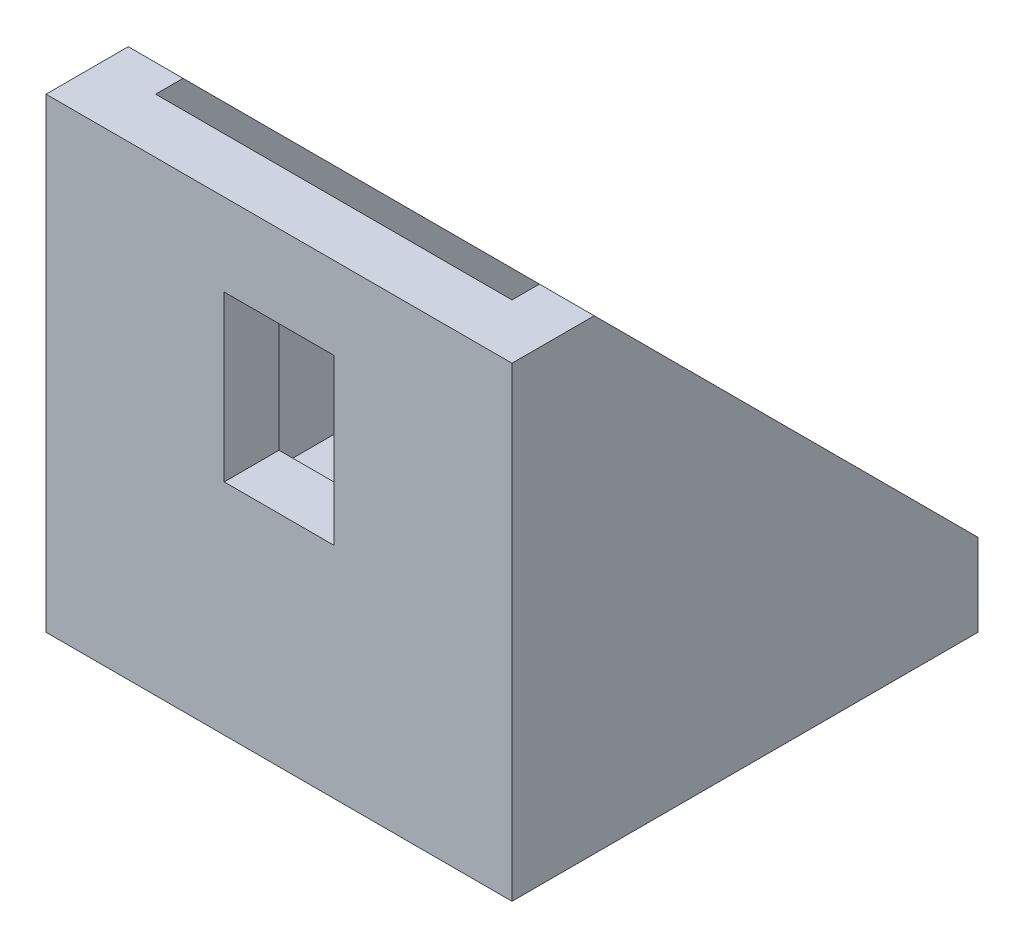
SolidWorks part; units mm, degrees
ref_plane "Front Plane" through (0, 0, 0) normal (0, 0, 1) x (1, 0, 0)
ref_plane "Top Plane" through (0, 0, 0) normal (0, 1, 0) x (1, 0, 0)
ref_plane "Right Plane" through (0, 0, 0) normal (1, 0, 0) x (0, 0, -1)
sketch "Sketch1" plane through (0, 0, 0) normal (1, 0, 0) x (0, 0, -1)
  line L0 (3, 17) -> (0, 17)
  line L1 (0, 17) -> (0, 0)
  line L2 (0, 0) -> (17, 0)
  line L3 (17, 0) -> (17, 3)
  line L4 (17, 3) -> (3, 17)
  dimension "D1" = 3
  dimension "D2" = 17
extrude "Body" add sketch "Sketch1" along normal mid plane 17
sketch "Sketch2" plane through (0, 0, -17) normal (0, 0, -1) x (-1, 0, 0)
  line L0 (-8.5, 3) -> (8.5, 3) construction
  line L1 (-6.5, 3) -> (6.5, 3)
  line L2 (-6.5, 3) -> (-6.5, 17)
  line L3 (-6.5, 17) -> (6.5, 17)
  line L4 (6.5, 3) -> (6.5, 17)
  line L5 (-8.5, 17) -> (8.5, 17) construction
  line L6 (8.5, 3) -> (8.5, 17) construction
  dimension "D1" = 2
  dimension "D2" = 2
extrude "Extusion" cut sketch "Sketch2" against normal offset from surface (15 mm away) 2 up to face at (0, 8.5, 0)
sketch "Sketch3" plane through (0, 0, -2) normal (0, 0, -1) x (-1, 0, 0)
  line L0 (-6.5, 17) -> (6.5, 17) construction
  line L7 (2, 8) -> (-2, 8)
  line L8 (2, 8) -> (2, 14)
  line L9 (2, 14) -> (-2, 14)
  line L10 (-2, 8) -> (-2, 14)
  line L11 (-6.5, 3) -> (-6.5, 17) construction
  line L13 (6.5, 17) -> (6.5, 3) construction
  point P6 (-2, 11)
  dimension "D1" = 3
  dimension "D2" = 4
  dimension "D3" = 6
  dimension "D4" = 4.5
extrude "Hole_A" cut sketch "Sketch3" against normal through all
sketch "Sketch4" plane through (0, 3, 0) normal (0, 1, 0) x (1, 0, 0)
  line L0 (6.5, 17) -> (-6.5, 17) construction
  line L3 (-2, 8) -> (2, 8)
  line L5 (-2, 8) -> (-2, 14)
  line L6 (-2, 14) -> (2, 14)
  line L7 (2, 8) -> (2, 14)
  line L8 (-6.5, 2) -> (-6.5, 17) construction
  dimension "D1" = 3
  dimension "D2" = 4
  dimension "D3" = 6
  dimension "D4" = 4.5
extrude "Hole_B" cut sketch "Sketch4" against normal blind 17
